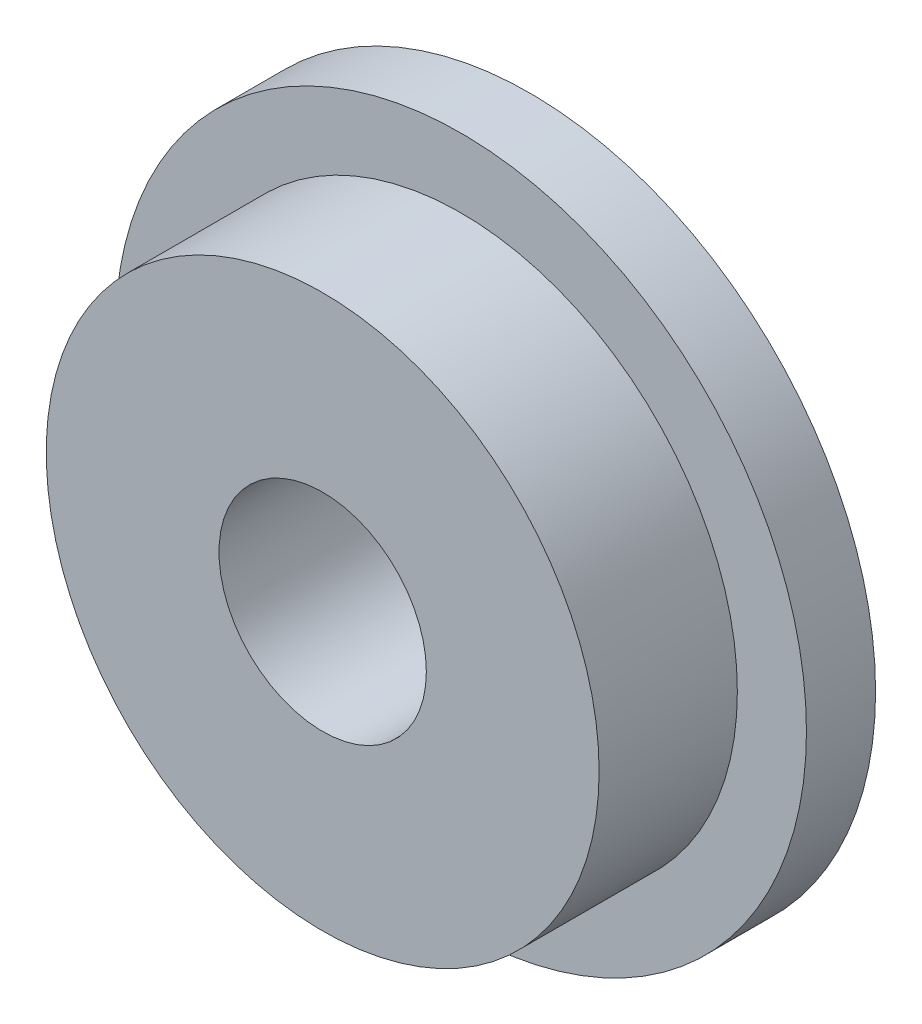
SolidWorks part; units mm, degrees
ref_plane "정면" through (0, 0, 0) normal (0, 0, 1) x (1, 0, 0)
ref_plane "윗면" through (0, 0, 0) normal (0, 1, 0) x (1, 0, 0)
ref_plane "우측면" through (0, 0, 0) normal (1, 0, 0) x (0, 0, -1)
sketch "스케치1" plane through (0, 0, 0) normal (0, 0, 1) x (1, 0, 0)
  circle A0 centre (0, 0) radius 5
  circle A1 centre (0, 0) radius 1.5
extrude "돌출1" add sketch "스케치1" along normal blind 1
sketch "스케치2" plane through (0, 0, 1) normal (0, 0, 1) x (1, 0, 0)
  circle A0 centre (0, 0) radius 4
extrude "돌출2" add sketch "스케치2" along normal blind 2
sketch "스케치3" plane through (0, 0, 3) normal (0, 0, 1) x (1, 0, 0)
  circle A0 centre (0, 0) radius 1.5
extrude "컷-돌출1" cut sketch "스케치3" against normal through all
